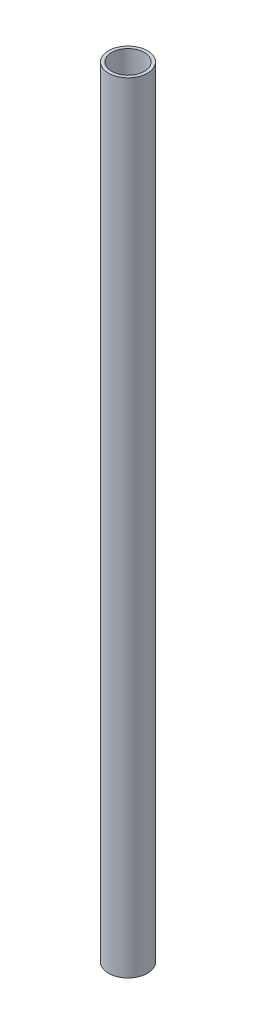
SolidWorks part; units mm, degrees
material "Hexcel AS4C (3000 Filaments)"
ref_plane "Front Plane" through (0, 0, 0) normal (0, 0, 1) x (1, 0, 0)
ref_plane "Top Plane" through (0, 0, 0) normal (0, 1, 0) x (1, 0, 0)
ref_plane "Right Plane" through (0, 0, 0) normal (1, 0, 0) x (0, 0, -1)
sketch "Sketch1" plane through (0, 0, 0) normal (0, 1, 0) x (1, 0, 0)
  circle A0 centre (0, 0) radius 12.5
  circle A1 centre (0, 0) radius 10.5
  dimension "D1" = 25
  dimension "D2" = 21
extrude "Boss-Extrude1" add sketch "Sketch1" along normal blind 500
